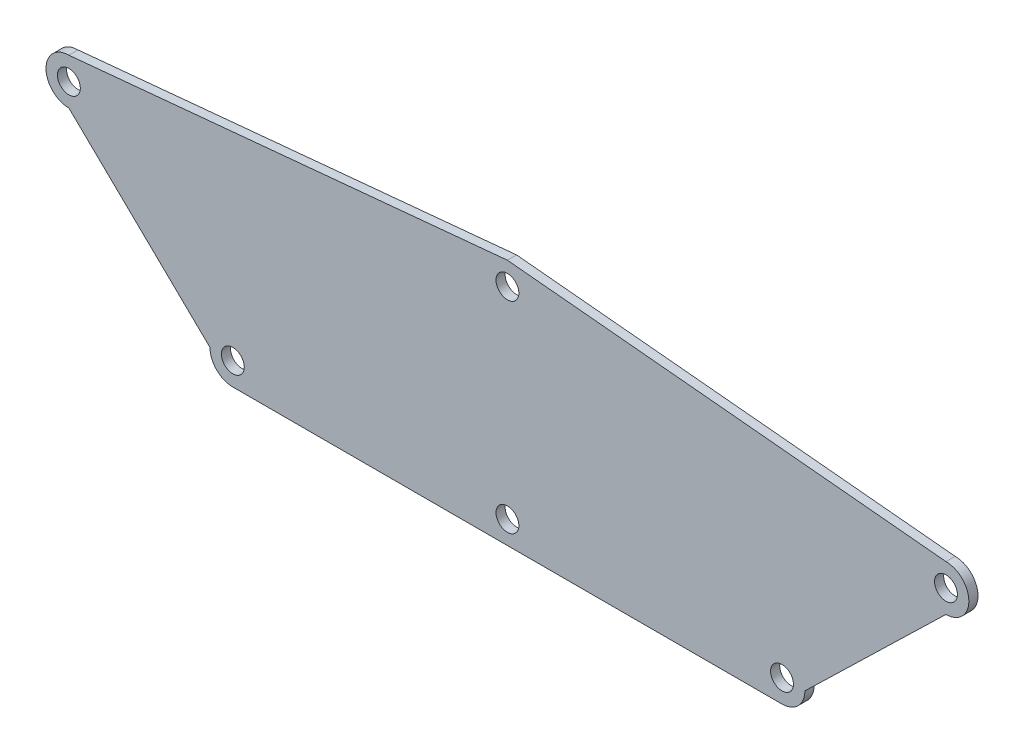
SolidWorks part; units mm, degrees
ref_plane "Front Plane" through (0, 0, 0) normal (0, 0, 1) x (1, 0, 0)
ref_plane "Top Plane" through (0, 0, 0) normal (0, 1, 0) x (1, 0, 0)
ref_plane "Right Plane" through (0, 0, 0) normal (1, 0, 0) x (0, 0, -1)
sketch "Sketch1" plane through (0, 0, 0) normal (0, 0, 1) x (1, 0, 0)
  line L0 (0, 0) -> (-60, 0) construction
  line L1 (0, 0) -> (60, 0) construction
  line L2 (0, 0) -> (0, 67.5618) construction
  line L3 (0, 0) -> (-144.0577, 52.4327) construction
  line L4 (0, 0) -> (129.844, 47.2594) construction
  line L5 (-95.8264, 39.8779) -> (0, 49)
  line L6 (0, 49) -> (95.8264, 39.8779)
  line L7 (95.8264, 29.8779) -> (65, 0)
  line L8 (60, -5) -> (0, -5)
  line L9 (0, -5) -> (-60, -5)
  line L10 (-95.8264, 29.8779) -> (-65, 0)
  circle A0 centre (0, 0) radius 5
  circle A1 centre (-60, 0) radius 5
  circle A2 centre (60, 0) radius 5
  circle A3 centre (0, 44) radius 5
  circle A4 centre (-95.8264, 34.8779) radius 5
  circle A5 centre (95.8264, 34.8779) radius 5
  circle A6 centre (-95.8264, 34.8779) radius 2.5
  circle A7 centre (0, 44) radius 2.5
  circle A8 centre (95.8264, 34.8779) radius 2.5
  circle A9 centre (60, 0) radius 2.5
  circle A10 centre (0, 0) radius 2.5
  circle A11 centre (-60, 0) radius 2.5
  dimension "D2" = 10
  dimension "D3" = 5
  dimension "D1" = 120
  dimension "D6" = 44
  dimension "D7" = 20
  dimension "D8" = 20
  dimension "D11" = 50
extrude "Boss-Extrude1" add sketch "Sketch1" along normal blind 2 contours A5 L6 A3 L5 A4 L10 A1 L9 A0 L8 A2 L7 | A4 A6 | L5 A3 L6 A7 | A5 A8 | A2 A9 | A0 A10 | A1 A11
